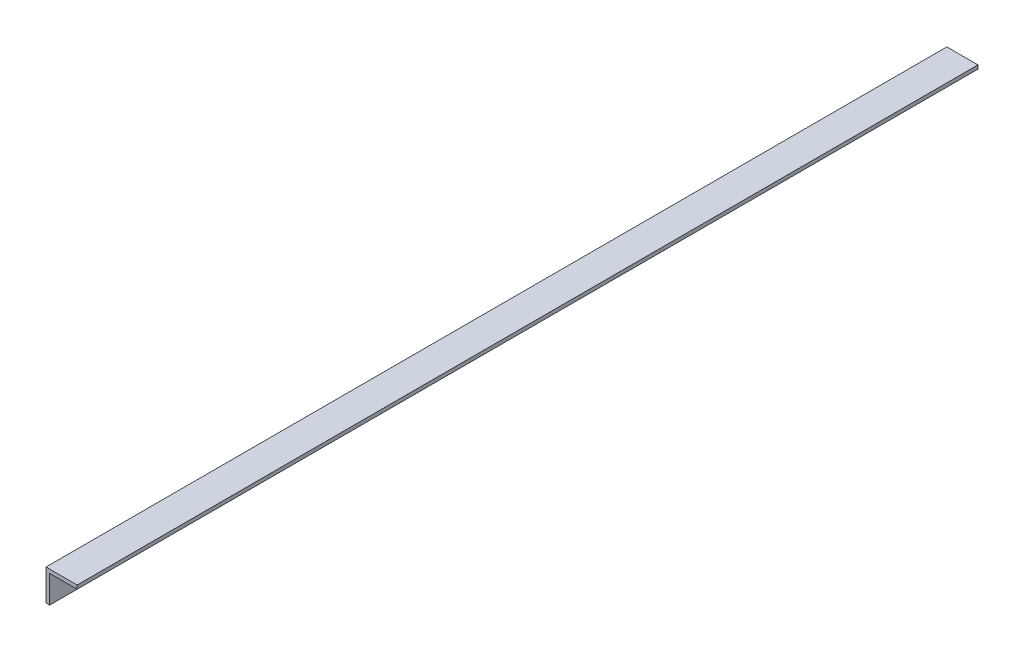
SolidWorks part; units mm, degrees
ref_plane "Alzado" through (0, 0, 0) normal (0, 0, 1) x (1, 0, 0)
ref_plane "Planta" through (0, 0, 0) normal (0, 1, 0) x (1, 0, 0)
ref_plane "Vista lateral" through (0, 0, 0) normal (1, 0, 0) x (0, 0, -1)
sketch "Croquis1" plane through (0, 0, 0) normal (0, 0, 1) x (1, 0, 0)
  line L0 (0, -1.5) -> (-11.2, -1.5)
  line L1 (0, 0) -> (-12.7, 0)
  line L2 (0, 0) -> (0, -1.5)
  line L3 (-11.2, -12.7) -> (-12.7, -12.7)
  line L4 (-12.7, 0) -> (-12.7, -12.7)
  line L5 (-11.2, -1.5) -> (-11.2, -12.7)
  dimension "D1" = 12.7
  dimension "D2" = 12.7
  dimension "D3" = 1.5
  dimension "D4" = 1.5
extrude "Saliente-Extruir1" add sketch "Croquis1" along normal blind 367.1
